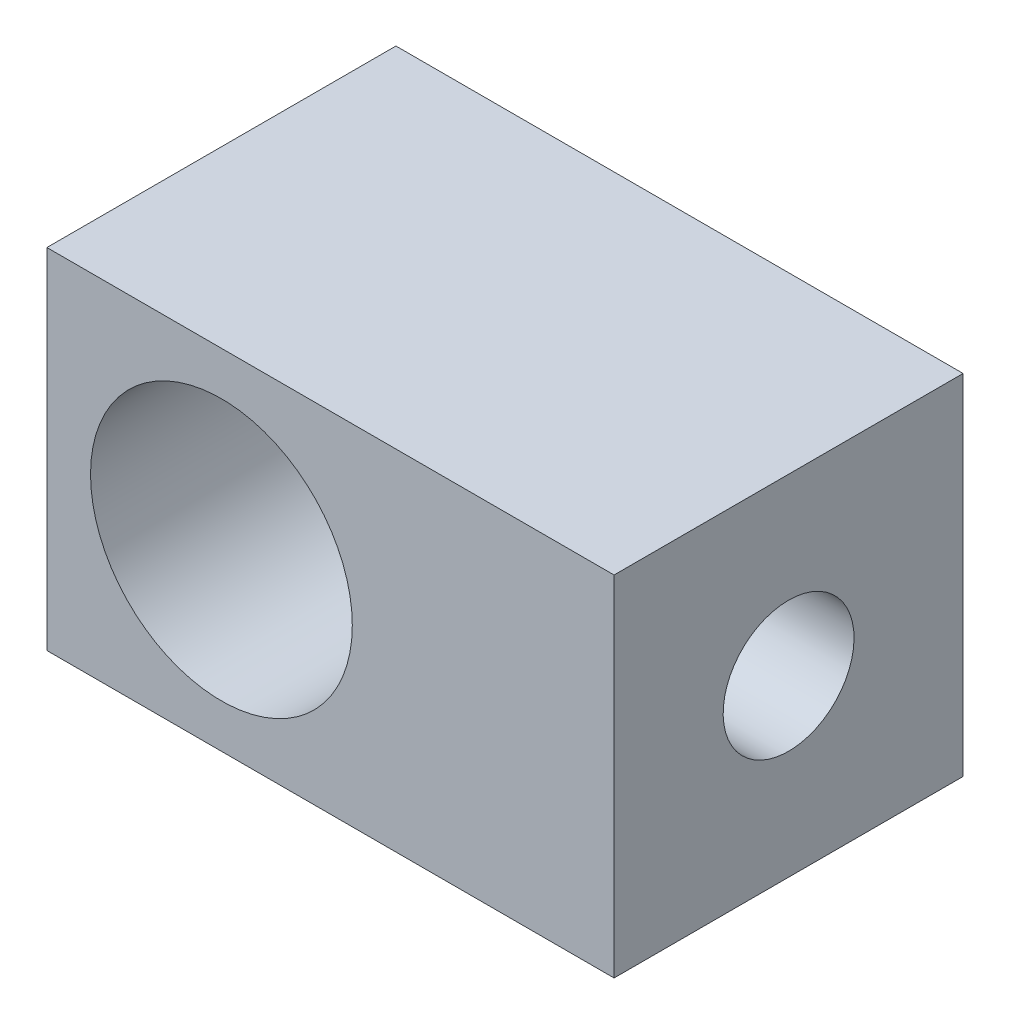
SolidWorks part; units mm, degrees
ref_plane "Front Plane" through (0, 0, 0) normal (0, 0, 1) x (1, 0, 0)
ref_plane "Top Plane" through (0, 0, 0) normal (0, 1, 0) x (1, 0, 0)
ref_plane "Right Plane" through (0, 0, 0) normal (1, 0, 0) x (0, 0, -1)
sketch "Sketch2" plane through (0, 0, 0) normal (0, 0, 1) x (1, 0, 0)
  line L1 (-4, 4) -> (4, 4)
  line L2 (-4, 4) -> (-4, -4)
  line L3 (-4, -4) -> (4, -4)
  line L4 (4, 4) -> (4, -4)
  line L5 (-4, 4) -> (4, -4) construction
  line L6 (-4, -4) -> (4, 4) construction
  point P0 (0, 0)
  dimension "D1" = 8
  dimension "D2" = 8
extrude "Boss-Extrude1" add sketch "Sketch2" along normal blind 8
sketch "Sketch3" plane through (0, 0, 8) normal (0, 0, 1) x (1, 0, 0)
  circle A0 centre (0, 0) radius 3
  dimension "D1" = 6
extrude "Cut-Extrude1" cut sketch "Sketch3" against normal blind 5
sketch "Sketch5" plane through (4, 0, 0) normal (1, 0, 0) x (0, 0, -1)
  line L0 (-8, 4) -> (-8, -4)
  line L1 (-8, -4) -> (0, -4)
  line L2 (0, -4) -> (0, 4)
  line L3 (0, 4) -> (-8, 4)
extrude "Boss-Extrude2" add sketch "Sketch5" along normal blind 5
sketch "Sketch6" plane through (9, 0, 0) normal (1, 0, 0) x (0, 0, -1)
  line L0 (0, 0) -> (-8, 0) construction
  line L3 (-8, 4) -> (-8, -4) construction
  line L5 (-4, 4) -> (-4, -4) construction
  line L6 (0, 4) -> (-8, 4) construction
  line L7 (-8, -4) -> (0, -4) construction
  circle A0 centre (-4, 0) radius 1.5
  dimension "D1" = 3
extrude "Cut-Extrude2" cut sketch "Sketch6" against normal blind 4
sketch "Sketch7" plane through (0, 0, 0) normal (0, 0, -1) x (-1, 0, 0)
  line L0 (-2.5, 4) -> (-2.5, -4) construction
  line L1 (-9, 4) -> (4, 4) construction
  line L2 (4, -4) -> (-9, -4) construction
  line L3 (-9, 0) -> (4, 0) construction
  line L4 (-9, -4) -> (-9, 4) construction
  line L5 (4, 4) -> (4, -4) construction
  line L6 (-2.5, 2.1213) -> (-0.3787, 0)
  line L7 (-2.5, 2.1213) -> (-4.6213, 0)
  line L8 (-0.3787, 0) -> (-2.5, -2.1213)
  line L9 (-4.6213, 0) -> (-2.5, -2.1213)
  line L10 (-2.5, 2.1213) -> (-2.5, -2.1213) construction
  line L11 (-0.3787, 0) -> (-4.6213, 0) construction
  point P12 (-2.5, 0)
  point P15 (-2.5, 0)
  dimension "D1" = 3
  dimension "D2" = 3
extrude "Cut-Extrude3" cut sketch "Sketch7" against normal blind 2.5
sketch "Sketch8" plane through (0, 0, 0) normal (0, 0, -1) x (-1, 0, 0)
  line L0 (-4.6213, 0) -> (-2.5, 2.1213)
  line L1 (-2.5, 2.1213) -> (-4.6213, 0) construction
  line L2 (-4.6213, 0) -> (-2.5, -2.1213) construction
  line L3 (-2.5, 2.1213) -> (-0.3787, 0)
  line L4 (-0.3787, 0) -> (-2.5, -2.1213)
  line L5 (-2.5, -2.1213) -> (-4.6213, 0)
extrude "Boss-Extrude4" add sketch "Sketch8" against normal blind 2
sketch "Sketch9" plane through (0, 0, 0) normal (0, 0, -1) x (-1, 0, 0)
  line L0 (-6.4874, 0) -> (-5.1487, 2.6848)
  line L1 (-5.1487, 2.6848) -> (-2.4639, 1.3461)
  line L2 (-2.4639, 1.3461) -> (-3.8026, -1.3387)
  line L4 (-6.4874, 0) -> (-3.8026, -1.3387)
  dimension "D1" = 3
  dimension "D2" = 3
  dimension "D3" = 3
extrude "Cut-Extrude4" cut sketch "Sketch9" against normal blind 1
sketch "Sketch10" plane through (0, 0, 0) normal (0, 0, -1) x (-1, 0, 0)
  line L0 (-5.1487, 2.6848) -> (-2.4639, 1.3461)
  line L1 (-2.4639, 1.3461) -> (-3.8026, -1.3387)
  line L2 (-3.8026, -1.3387) -> (-6.4874, 0)
  line L3 (-6.4874, 0) -> (-5.1487, 2.6848)
extrude "Boss-Extrude5" add sketch "Sketch10" against normal blind 2
sketch "Sketch11" plane through (0, 0, 0) normal (0, 0, -1) x (-1, 0, 0)
  line L0 (-2.5, 4) -> (-2.5, -4) construction
  line L1 (-9, 4) -> (4, 4) construction
  line L2 (4, -4) -> (-9, -4) construction
  line L3 (-9, 0) -> (4, 0) construction
  line L4 (-9, -4) -> (-9, 4) construction
  line L5 (4, 4) -> (4, -4) construction
  line L7 (-4, 1.5) -> (-1, 1.5)
  line L8 (-4, 1.5) -> (-4, -1.5)
  line L9 (-4, -1.5) -> (-1, -1.5)
  line L10 (-1, 1.5) -> (-1, -1.5)
  line L11 (-4, 1.5) -> (-1, -1.5) construction
  line L12 (-4, -1.5) -> (-1, 1.5) construction
  point P12 (-2.5, 0)
  dimension "D1" = 3
  dimension "D2" = 3
extrude "Cut-Extrude8" cut sketch "Sketch11" against normal blind 2.5
